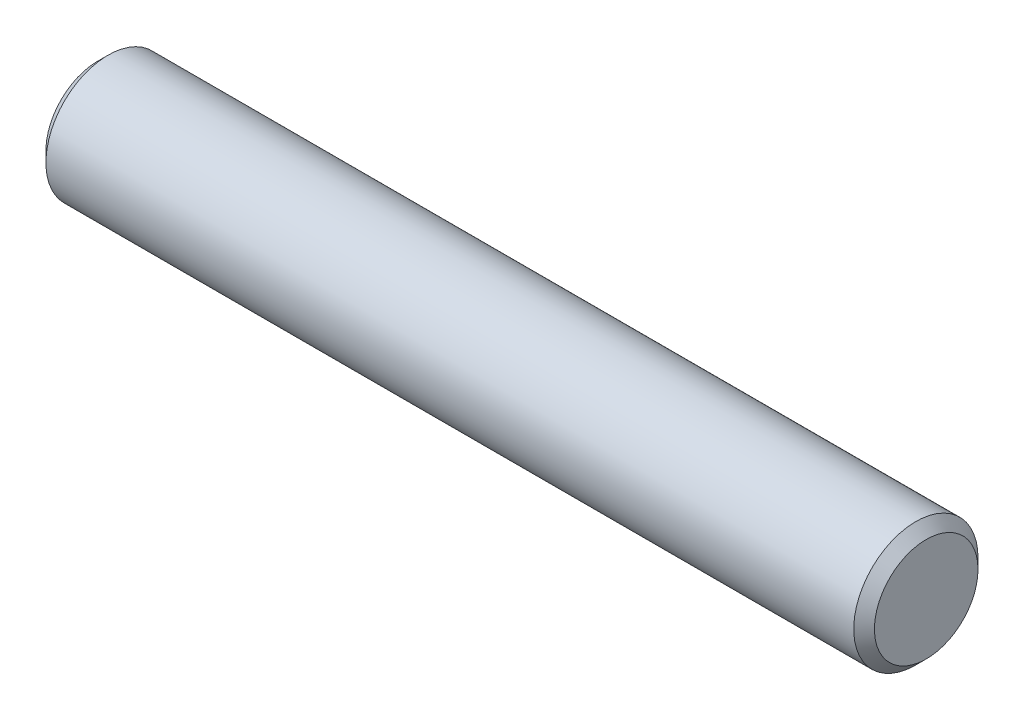
SolidWorks part; units mm, degrees
ref_plane "Спереди" through (0, 0, 0) normal (0, 0, 1) x (1, 0, 0)
ref_plane "Сверху" through (0, 0, 0) normal (0, 1, 0) x (1, 0, 0)
ref_plane "Справа" through (0, 0, 0) normal (1, 0, 0) x (0, 0, -1)
sketch "Эскиз1" plane through (0, 0, 0) normal (1, 0, 0) x (0, 0, -1)
  circle A0 centre (0, 0) radius 3
  dimension "D1" = 6
extrude "Бобышка-Вытянуть1" add sketch "Эскиз1" along normal mid plane 40
chamfer "Фаска1" distance 0.5 angle 45 2 edges at (-20, 0, -3) (20, 0, -3)
